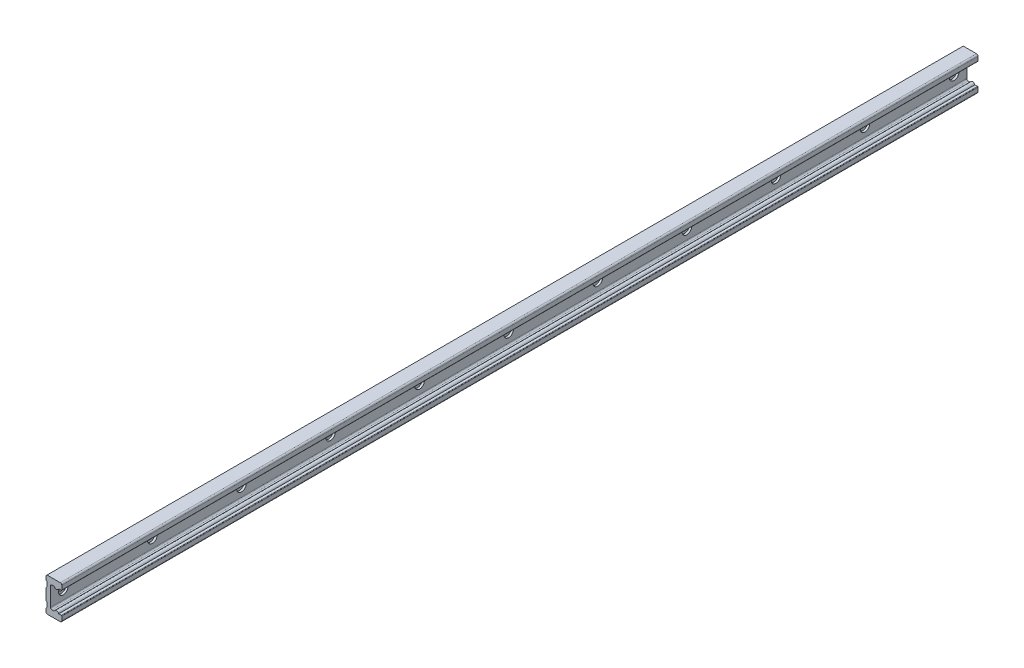
SolidWorks part; units mm, degrees
ref_plane "Front" through (0, 0, 0) normal (0, 0, 1) x (1, 0, 0)
ref_plane "Top" through (0, 0, 0) normal (0, 1, 0) x (1, 0, 0)
ref_plane "Right" through (0, 0, 0) normal (1, 0, 0) x (0, 0, -1)
sketch "Sketch1" plane through (0, 0, 0) normal (0, 0, 1) x (1, 0, 0)
  line L0 (5.334, 11.303) -> (5.334, 15.367)
  line L1 (3.81, 16.891) -> (-9.398, 16.891)
  line L2 (-10.414, 15.875) -> (-10.414, 12.192)
  line L3 (-10.414, 12.192) -> (-9.652, 11.43)
  line L4 (-9.652, 11.43) -> (-9.652, 6.35)
  line L5 (-9.652, 6.35) -> (-10.414, 5.588)
  line L6 (-10.414, 5.588) -> (-10.414, -5.588)
  line L7 (-10.414, -5.588) -> (-9.652, -6.35)
  line L8 (-9.652, -6.35) -> (-9.652, -11.43)
  line L9 (-9.652, -11.43) -> (-10.414, -12.192)
  line L10 (-10.414, -12.192) -> (-10.414, -15.875)
  line L11 (-10.414, 0) -> (-5.842, 0) construction
  line L12 (-5.842, 0) -> (0, 0) construction
  line L13 (-5.842, 9.271) -> (-5.842, 16.891) construction
  line L14 (-5.842, -9.271) -> (-5.842, -16.891) construction
  line L15 (-9.398, -16.891) -> (3.81, -16.891)
  line L16 (5.334, -15.367) -> (5.334, -11.303)
  line L17 (4.826, -10.795) -> (2.2627, -10.795)
  line L18 (-2.2627, -10.795) -> (-4.318, -10.795)
  line L19 (-5.842, -9.271) -> (-5.842, 9.271)
  line L20 (-4.318, 10.795) -> (-2.2627, 10.795)
  line L21 (2.2627, 10.795) -> (4.826, 10.795)
  line L22 (0, 9.1694) -> (0, -9.1694) construction
  line L23 (-10.414, 15.875) -> (-9.398, 16.891)
  line L24 (-10.414, -15.875) -> (-9.398, -16.891)
  arc A0 (4.826, 10.795) -> (5.334, 11.303) centre (4.826, 11.303) ccw
  arc A1 (5.334, 15.367) -> (3.81, 16.891) centre (3.81, 15.367) ccw
  arc A4 (3.81, -16.891) -> (5.334, -15.367) centre (3.81, -15.367) ccw
  arc A5 (5.334, -11.303) -> (4.826, -10.795) centre (4.826, -11.303) ccw
  arc A6 (2.2627, -10.795) -> (-2.2627, -10.795) centre (0, -11.557) ccw
  arc A7 (-5.842, -9.271) -> (-4.318, -10.795) centre (-4.318, -9.271) ccw
  arc A8 (-4.318, 10.795) -> (-5.842, 9.271) centre (-4.318, 9.271) ccw
  arc A9 (-2.2627, 10.795) -> (2.2627, 10.795) centre (0, 11.557) ccw
  dimension "D2" = 45
  dimension "Ball Radius" = 2.3876
  dimension "Nose Radius 1" = 1.524
  dimension "Nose Radius 2" = 0.508
  dimension "Nose Radius 3" = 1.524
  dimension "D3" = 1.016
  dimension "D1" = 45
  dimension "Ht" = 33.782
  dimension "Center Offset" = 10.414
  dimension "Wd" = 15.748
  dimension "Inner Ht 2" = 21.59
  dimension "Jog Offset" = 0.762
  dimension "Jog Ht Mid" = 11.176
  dimension "Jog Ht Upper" = 5.08
  dimension "Spine Thickness" = 4.572
  dimension "Center to Center" = 23.114
extrude "Boss-Extrude1" add sketch "Sketch1" along normal mid plane 914.4
ref_plane "Plane1" through (0, 0, 444.5) normal (0, 0, 1) x (1, 0, 0)
sketch "Sketch3" plane through (0, 0, 444.5) normal (0, 0, 1) x (1, 0, 0)
  line L0 (-5.842, 4.7625) -> (-8.0518, 4.7625)
  line L1 (-8.0518, 4.7625) -> (-8.0518, 2.4638)
  line L2 (-8.0518, 2.4638) -> (-10.414, 2.4638)
  line L3 (-10.414, 2.4638) -> (-10.414, 0)
  line L4 (-10.414, 0) -> (-5.842, 0)
  line L5 (-5.842, 0) -> (-5.842, 4.7625)
  line L6 (-5.842, 4.7625) -> (-5.842, -4.7625) construction
  line L7 (-10.414, 2.4638) -> (-10.414, -2.4638) construction
  line L8 (-10.414, 5.588) -> (-10.414, -5.588) construction
  line L9 (-5.842, -9.271) -> (-5.842, 9.271) construction
  dimension "Outer Hole Dia" = 9.525
  dimension "Inner Hole Dia" = 4.9276
  dimension "Outer Hole Dp" = 2.2098
revolve "Cut-Revolve1" cut sketch "Sketch3" angle 360 mid plane about L4
pattern_linear "LPattern1" count 11 spacing 88.9 along (0, 0, -1) of "Cut-Revolve1"
sketch "Sketch4" plane through (0, 0, 0) normal (0, 0, 1) x (1, 0, 0)
  line L0 (-8.0518, -4.7625) -> (-5.842, -4.7625) construction
  line L1 (-8.0518, -4.7625) -> (-8.0518, 4.7625) construction
  line L2 (-10.414, -2.4638) -> (-8.0518, -2.4638) construction
  line L3 (-8.0518, 2.4638) -> (-10.414, 2.4638) construction
  line L4 (-5.842, 4.7625) -> (-8.0518, 4.7625) construction
  line L5 (-8.0518, -4.7625) -> (-5.842, -4.7625)
  line L6 (-8.0518, -4.7625) -> (-8.0518, 4.7625)
  line L7 (-10.414, -2.4638) -> (-8.0518, -2.4638)
  line L8 (-8.0518, 2.4638) -> (-10.414, 2.4638)
  line L9 (-5.842, 4.7625) -> (-8.0518, 4.7625)
sketch "K73" plane through (0, 0, 0) normal (0, 0, 1) x (1, 0, 0)
  line B0 (5.969, -15.875) -> (13.8938, -15.875)
  line B1 (13.8938, -15.875) -> (13.8938, 15.875)
  line B2 (13.8938, 15.875) -> (5.969, 15.875)
  line B3 (5.969, 15.875) -> (5.969, 5.8458)
  line B4 (1.8798, -10.081) -> (2.921, -10.081)
  line B5 (2.921, -10.081) -> (3.937, -9.065)
  line B6 (3.937, -9.065) -> (3.937, -5.8458)
  line B7 (-3.937, 9.065) -> (-3.937, -9.065)
  line B8 (-2.921, -10.081) -> (-1.8798, -10.081)
  line B9 (-3.937, -9.065) -> (-2.921, -10.081)
  line B10 (3.937, -5.8458) -> (5.969, -5.8458)
  line B11 (5.969, 5.8458) -> (3.937, 5.8458)
  line B12 (3.937, 9.065) -> (2.921, 10.081)
  line B13 (2.921, 10.081) -> (1.8798, 10.081)
  line B14 (-1.8798, 10.081) -> (-2.921, 10.081)
  line B15 (-2.921, 10.081) -> (-3.937, 9.065)
  line B16 (5.969, -5.8458) -> (5.969, -15.875)
  line B17 (3.937, 5.8458) -> (3.937, 9.065)
  line B18 (0, 9.217) -> (0, -9.217) construction
  arc B19 (1.8798, -10.081) -> (-1.8798, -10.081) centre (0, -11.694) ccw
  arc B20 (-1.8798, 10.081) -> (1.8798, 10.081) centre (0, 11.694) ccw
sketch_block_instance "Block2-1"
sketch_block "Block2"
sketch "K72" plane through (0, 0, 0) normal (0, 0, 1) x (1, 0, 0)
  line B0 (7.5908, -18.956) -> (15.3525, -18.956)
  line B1 (15.3525, -18.956) -> (15.3525, 19.144)
  line B2 (15.3525, 19.144) -> (7.5908, 19.144)
  line B3 (7.5908, 19.144) -> (7.5908, 8.3134)
  line B4 (-2.659, 15.7429) -> (-4.2852, 15.7429)
  line B5 (-4.2852, 15.7429) -> (-5.5552, 14.4729)
  line B6 (-5.5552, 14.4729) -> (-5.5552, -14.4729)
  line B7 (4.2878, 15.7429) -> (2.659, 15.7429)
  line B8 (5.5578, 14.4729) -> (4.2878, 15.7429)
  line B9 (5.5578, -14.4729) -> (5.5578, -8.3134)
  line B10 (7.5908, 8.3134) -> (5.5578, 8.3134)
  line B11 (4.2878, -15.7429) -> (5.5578, -14.4729)
  line B12 (2.659, -15.7429) -> (4.2878, -15.7429)
  line B13 (-4.2852, -15.7429) -> (-2.659, -15.7429)
  line B14 (-5.5552, -14.4729) -> (-4.2852, -15.7429)
  line B15 (5.5578, -8.3134) -> (7.5908, -8.3134)
  line B16 (7.5908, -8.3134) -> (7.5908, -18.956)
  line B17 (5.5578, 8.3134) -> (5.5578, 14.4729)
  line B18 (0, -14.3969) -> (0, 14.3969) construction
  arc B19 (2.659, -15.7429) -> (-2.659, -15.7429) centre (0, -17.6963) ccw
  arc B20 (-2.659, 15.7429) -> (2.659, 15.7429) centre (0, 17.6963) ccw
sketch_block_instance "Block1-1"
sketch_block "Block1" parameters "D1"=27.1398
